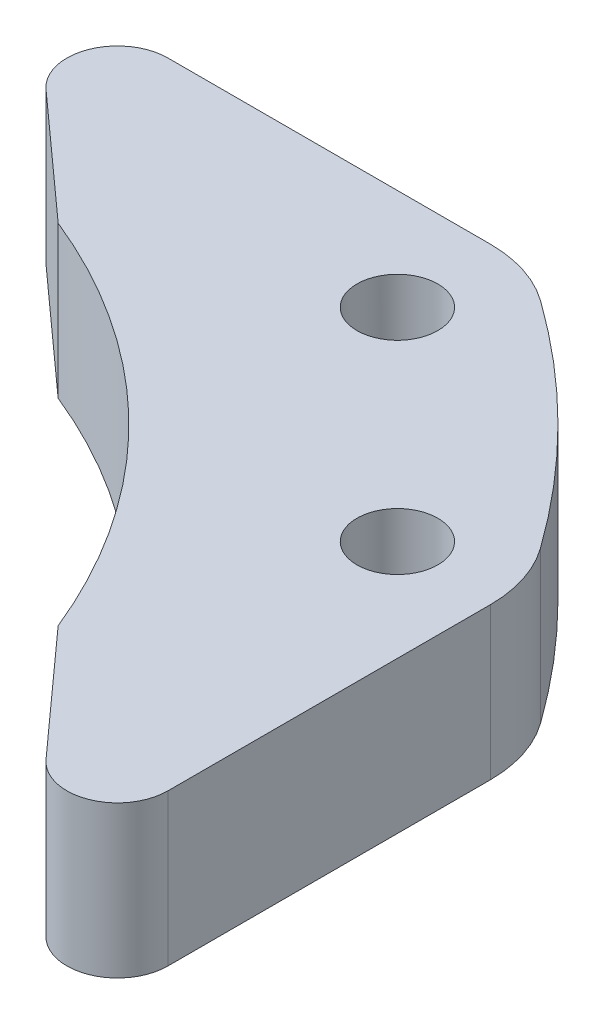
SolidWorks part; units mm, degrees
material "5052-H32"
ref_plane "前视基准面" through (0, 0, 0) normal (0, 0, 1) x (1, 0, 0)
ref_plane "上视基准面" through (0, 0, 0) normal (0, 1, 0) x (1, 0, 0)
ref_plane "右视基准面" through (0, 0, 0) normal (1, 0, 0) x (0, 0, -1)
other "Configuration Table"
sketch "草图1" plane through (0, 0, 0) normal (0, 1, 0) x (1, 0, 0)
  line L0 (-20.199, 31) -> (20.199, 31)
  line L5 (31, 20.199) -> (31, -20.199)
  arc A0 (-20.199, 31) -> (31, -20.199) centre (0, 0) ccw
  arc A1 (31, 20.199) -> (20.199, 31) centre (0, 0) ccw
  dimension "D1" = 74
  dimension "D2" = 31
  dimension "D3" = 31
extrude "凸台-拉伸1" add sketch "草图1" along normal blind 6
sketch "草图2" plane through (0, 6, 0) normal (0, 1, 0) x (1, 0, 0)
  line L0 (0, 0) -> (33, 0) construction
  line L1 (0, 0) -> (26.9989, 18.9752) construction
  line L2 (0, 0) -> (23.3345, 23.3345) construction
  circle A0 centre (0, 0) radius 33 construction
  circle A1 centre (26.9989, 18.9752) radius 1.6
  circle A2 centre (18.9752, 26.9989) radius 1.6
  dimension "D1" = 66
  dimension "D3" = 3.2
  dimension "D2" = 35.1
  dimension "D4" = 45
extrude "切除-拉伸1" cut sketch "草图2" against normal blind 10
sketch "草图3" plane through (0, 6, 0) normal (0, 1, 0) x (1, 0, 0)
  line L0 (0, 0) -> (-39.5427, 35.6044) construction
  line L1 (0, 0) -> (0, 31) construction
  line L2 (20.199, 31) -> (-20.199, 31) construction
  line L3 (0.6912, 31) -> (9.386, 23.1712)
  line L4 (0, 0) -> (26.163, 26.163) construction
  line L5 (20.199, 31) -> (0.6912, 31)
  line L6 (31, 0.6912) -> (23.1712, 9.386)
  line L7 (31, -20.199) -> (31, 20.199) construction
  line L8 (31, 0.6912) -> (31, 20.199)
  arc A0 (23.1712, 9.386) -> (9.386, 23.1712) centre (0, 0) ccw
  arc A1 (31, 20.199) -> (20.199, 31) centre (0, 0) ccw construction
  arc A2 (31, 20.199) -> (20.199, 31) centre (0, 0) ccw
  dimension "D3" = 50
  dimension "D1" = 48
  dimension "D2" = 23.5
extrude "切除-拉伸2" cut sketch "草图3" against normal blind 10 flip side to cut
fillet "圆角1" radius 5 2 edges at (31, 3, -20.199) (20.199, 3, -31)
fillet "圆角2" radius 2 2 edges at (31, 3, -0.6912) (0.6912, 3, -31)
